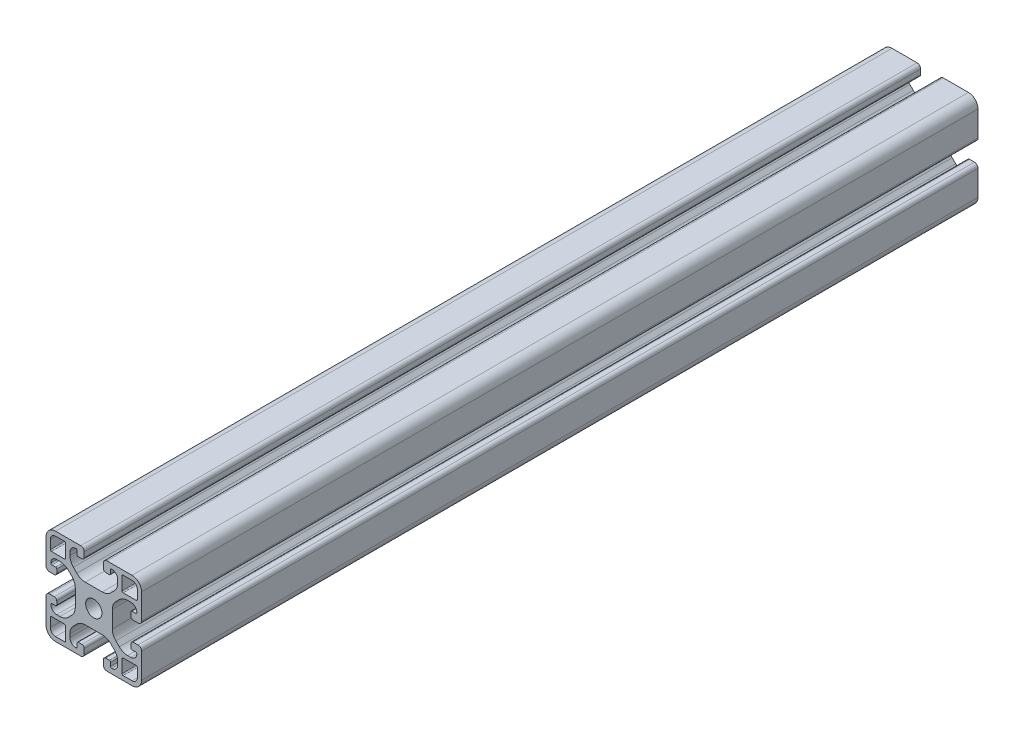
SolidWorks part; units mm, degrees
ref_plane "Plan de face" through (0, 0, 0) normal (0, 0, 1) x (1, 0, 0)
ref_plane "Plan de dessus" through (0, 0, 0) normal (0, 1, 0) x (1, 0, 0)
ref_plane "Plan de droite" through (0, 0, 0) normal (1, 0, 0) x (0, 0, -1)
ref_plane "Plan1" through (0, 0, -30) normal (0, 0, -1) x (-1, 0, 0)
sketch "Esquisse1" plane through (0, 0, -30) normal (0, 0, -1) x (-1, 0, 0)
  line L0 (-4.5, 15) -> (-4.5, 13.5)
  line L1 (-4, 13) -> (-2.5, 13)
  line L2 (-4.5, 10) -> (-5.8076, 10)
  line L3 (-9.3431, 11.4645) -> (-10.7855, 12.9069)
  line L4 (-12.25, 16.4424) -> (-12.25, 23.5576)
  line L5 (-10.7855, 27.0931) -> (-9.3431, 28.5355)
  line L6 (-5.8076, 30) -> (-4.5, 30)
  line L7 (-2.5, 27) -> (-4, 27)
  line L8 (-4.5, 26.5) -> (-4.5, 25)
  line L9 (-3.5, 24) -> (-1.5, 24)
  line L10 (0, 25.5) -> (0, 36)
  line L11 (-4, 40) -> (-14.5, 40)
  line L12 (-16, 38.5) -> (-16, 36.5)
  line L13 (-15, 35.5) -> (-13.5, 35.5)
  line L14 (-13, 36) -> (-13, 37.5)
  line L15 (-10, 35.5) -> (-10, 34.1924)
  line L16 (-11.4645, 30.6569) -> (-12.9069, 29.2145)
  line L17 (-16.4424, 27.75) -> (-23.5576, 27.75)
  line L18 (-27.0931, 29.2145) -> (-28.5355, 30.6569)
  line L19 (-30, 34.1924) -> (-30, 35.5)
  line L20 (-27, 37.5) -> (-27, 36)
  line L21 (-26.5, 35.5) -> (-25, 35.5)
  line L22 (-24, 36.5) -> (-24, 38.5)
  line L23 (-25.5, 40) -> (-36, 40)
  line L24 (-40, 36) -> (-40, 25.5)
  line L25 (-38.5, 24) -> (-36.5, 24)
  line L26 (-35.5, 25) -> (-35.5, 26.5)
  line L27 (-36, 27) -> (-37.5, 27)
  line L28 (-35.5, 30) -> (-34.1924, 30)
  line L29 (-30.6569, 28.5355) -> (-29.2145, 27.0931)
  line L30 (-27.75, 23.5576) -> (-27.75, 16.4424)
  line L31 (-29.2145, 12.9069) -> (-30.6569, 11.4645)
  line L32 (-34.1924, 10) -> (-35.5, 10)
  line L33 (-37.5, 13) -> (-36, 13)
  line L34 (-35.5, 13.5) -> (-35.5, 15)
  line L35 (-36.5, 16) -> (-38.5, 16)
  line L36 (-40, 14.5) -> (-40, 4)
  line L37 (-36, 0) -> (-25.5, 0)
  line L38 (-24, 1.5) -> (-24, 3.5)
  line L39 (-25, 4.5) -> (-26.5, 4.5)
  line L40 (-27, 4) -> (-27, 2.5)
  line L41 (-30, 4.5) -> (-30, 5.8076)
  line L42 (-28.5355, 9.3431) -> (-27.0931, 10.7855)
  line L43 (-23.5576, 12.25) -> (-16.4424, 12.25)
  line L44 (-12.9069, 10.7855) -> (-11.4645, 9.3431)
  line L45 (-10, 5.8076) -> (-10, 4.5)
  line L46 (-13, 2.5) -> (-13, 4)
  line L47 (-13.5, 4.5) -> (-15, 4.5)
  line L48 (-16, 3.5) -> (-16, 1.5)
  line L49 (-14.5, 0) -> (-4, 0)
  line L50 (0, 4) -> (0, 14.5)
  line L51 (-1.5, 16) -> (-3.5, 16)
  line L52 (-4, 1.8) -> (-7.7, 1.8)
  line L53 (-8.2, 2.3) -> (-8.2, 7.7)
  line L54 (-7.7, 8.2) -> (-2.3, 8.2)
  line L55 (-1.8, 7.7) -> (-1.8, 4)
  line L56 (-38.2, 4) -> (-38.2, 7.7)
  line L57 (-37.7, 8.2) -> (-32.3, 8.2)
  line L58 (-31.8, 7.7) -> (-31.8, 2.3)
  line L59 (-32.3, 1.8) -> (-36, 1.8)
  line L60 (-36, 38.2) -> (-32.3, 38.2)
  line L61 (-31.8, 37.7) -> (-31.8, 32.3)
  line L62 (-32.3, 31.8) -> (-37.7, 31.8)
  line L63 (-38.2, 32.3) -> (-38.2, 36)
  line L64 (-1.8, 36) -> (-1.8, 32.3)
  line L65 (-2.3, 31.8) -> (-7.7, 31.8)
  line L66 (-8.2, 32.3) -> (-8.2, 37.7)
  line L67 (-7.7, 38.2) -> (-4, 38.2)
  arc A0 (-4.5, 13.5) -> (-4, 13) centre (-4, 13.5) ccw
  arc A1 (-2.5, 13) -> (-2, 12.5) centre (-2.5, 12.5) cw
  arc A2 (-2, 12.5) -> (-4.5, 10) centre (-4.5, 12.5) cw
  arc A3 (-5.8076, 10) -> (-9.3431, 11.4645) centre (-5.8076, 15) cw
  arc A4 (-10.7855, 12.9069) -> (-12.25, 16.4424) centre (-7.25, 16.4424) cw
  arc A5 (-12.25, 23.5576) -> (-10.7855, 27.0931) centre (-7.25, 23.5576) cw
  arc A6 (-9.3431, 28.5355) -> (-5.8076, 30) centre (-5.8076, 25) cw
  arc A7 (-4.5, 30) -> (-2, 27.5) centre (-4.5, 27.5) cw
  arc A8 (-2, 27.5) -> (-2.5, 27) centre (-2.5, 27.5) cw
  arc A9 (-4, 27) -> (-4.5, 26.5) centre (-4, 26.5) ccw
  arc A10 (-4.5, 25) -> (-3.5, 24) centre (-3.5, 25) ccw
  arc A11 (-1.5, 24) -> (0, 25.5) centre (-1.5, 25.5) ccw
  arc A12 (0, 36) -> (-4, 40) centre (-4, 36) ccw
  arc A13 (-14.5, 40) -> (-16, 38.5) centre (-14.5, 38.5) ccw
  arc A14 (-16, 36.5) -> (-15, 35.5) centre (-15, 36.5) ccw
  arc A15 (-13.5, 35.5) -> (-13, 36) centre (-13.5, 36) ccw
  arc A16 (-13, 37.5) -> (-12.5, 38) centre (-12.5, 37.5) cw
  arc A17 (-12.5, 38) -> (-10, 35.5) centre (-12.5, 35.5) cw
  arc A18 (-10, 34.1924) -> (-11.4645, 30.6569) centre (-15, 34.1924) cw
  arc A19 (-12.9069, 29.2145) -> (-16.4424, 27.75) centre (-16.4424, 32.75) cw
  arc A20 (-23.5576, 27.75) -> (-27.0931, 29.2145) centre (-23.5576, 32.75) cw
  arc A21 (-28.5355, 30.6569) -> (-30, 34.1924) centre (-25, 34.1924) cw
  arc A22 (-30, 35.5) -> (-27.5, 38) centre (-27.5, 35.5) cw
  arc A23 (-27.5, 38) -> (-27, 37.5) centre (-27.5, 37.5) cw
  arc A24 (-27, 36) -> (-26.5, 35.5) centre (-26.5, 36) ccw
  arc A25 (-25, 35.5) -> (-24, 36.5) centre (-25, 36.5) ccw
  arc A26 (-24, 38.5) -> (-25.5, 40) centre (-25.5, 38.5) ccw
  arc A27 (-36, 40) -> (-40, 36) centre (-36, 36) ccw
  arc A28 (-40, 25.5) -> (-38.5, 24) centre (-38.5, 25.5) ccw
  arc A29 (-36.5, 24) -> (-35.5, 25) centre (-36.5, 25) ccw
  arc A30 (-35.5, 26.5) -> (-36, 27) centre (-36, 26.5) ccw
  arc A31 (-37.5, 27) -> (-38, 27.5) centre (-37.5, 27.5) cw
  arc A32 (-38, 27.5) -> (-35.5, 30) centre (-35.5, 27.5) cw
  arc A33 (-34.1924, 30) -> (-30.6569, 28.5355) centre (-34.1924, 25) cw
  arc A34 (-29.2145, 27.0931) -> (-27.75, 23.5576) centre (-32.75, 23.5576) cw
  arc A35 (-27.75, 16.4424) -> (-29.2145, 12.9069) centre (-32.75, 16.4424) cw
  arc A36 (-30.6569, 11.4645) -> (-34.1924, 10) centre (-34.1924, 15) cw
  arc A37 (-35.5, 10) -> (-38, 12.5) centre (-35.5, 12.5) cw
  arc A38 (-38, 12.5) -> (-37.5, 13) centre (-37.5, 12.5) cw
  arc A39 (-36, 13) -> (-35.5, 13.5) centre (-36, 13.5) ccw
  arc A40 (-35.5, 15) -> (-36.5, 16) centre (-36.5, 15) ccw
  arc A41 (-38.5, 16) -> (-40, 14.5) centre (-38.5, 14.5) ccw
  arc A42 (-40, 4) -> (-36, 0) centre (-36, 4) ccw
  arc A43 (-25.5, 0) -> (-24, 1.5) centre (-25.5, 1.5) ccw
  arc A44 (-24, 3.5) -> (-25, 4.5) centre (-25, 3.5) ccw
  arc A45 (-26.5, 4.5) -> (-27, 4) centre (-26.5, 4) ccw
  arc A46 (-27, 2.5) -> (-27.5, 2) centre (-27.5, 2.5) cw
  arc A47 (-27.5, 2) -> (-30, 4.5) centre (-27.5, 4.5) cw
  arc A48 (-30, 5.8076) -> (-28.5355, 9.3431) centre (-25, 5.8076) cw
  arc A49 (-27.0931, 10.7855) -> (-23.5576, 12.25) centre (-23.5576, 7.25) cw
  arc A50 (-16.4424, 12.25) -> (-12.9069, 10.7855) centre (-16.4424, 7.25) cw
  arc A51 (-11.4645, 9.3431) -> (-10, 5.8076) centre (-15, 5.8076) cw
  arc A52 (-10, 4.5) -> (-12.5, 2) centre (-12.5, 4.5) cw
  arc A53 (-12.5, 2) -> (-13, 2.5) centre (-12.5, 2.5) cw
  arc A54 (-13, 4) -> (-13.5, 4.5) centre (-13.5, 4) ccw
  arc A55 (-15, 4.5) -> (-16, 3.5) centre (-15, 3.5) ccw
  arc A56 (-16, 1.5) -> (-14.5, 0) centre (-14.5, 1.5) ccw
  arc A57 (-4, 0) -> (0, 4) centre (-4, 4) ccw
  arc A58 (0, 14.5) -> (-1.5, 16) centre (-1.5, 14.5) ccw
  arc A59 (-3.5, 16) -> (-4.5, 15) centre (-3.5, 15) ccw
  circle A60 centre (-20, 20) radius 3.4
  arc A61 (-1.8, 4) -> (-4, 1.8) centre (-4, 4) cw
  arc A62 (-7.7, 1.8) -> (-8.2, 2.3) centre (-7.7, 2.3) cw
  arc A63 (-8.2, 7.7) -> (-7.7, 8.2) centre (-7.7, 7.7) cw
  arc A64 (-2.3, 8.2) -> (-1.8, 7.7) centre (-2.3, 7.7) cw
  arc A65 (-36, 1.8) -> (-38.2, 4) centre (-36, 4) cw
  arc A66 (-38.2, 7.7) -> (-37.7, 8.2) centre (-37.7, 7.7) cw
  arc A67 (-32.3, 8.2) -> (-31.8, 7.7) centre (-32.3, 7.7) cw
  arc A68 (-31.8, 2.3) -> (-32.3, 1.8) centre (-32.3, 2.3) cw
  arc A69 (-38.2, 36) -> (-36, 38.2) centre (-36, 36) cw
  arc A70 (-32.3, 38.2) -> (-31.8, 37.7) centre (-32.3, 37.7) cw
  arc A71 (-31.8, 32.3) -> (-32.3, 31.8) centre (-32.3, 32.3) cw
  arc A72 (-37.7, 31.8) -> (-38.2, 32.3) centre (-37.7, 32.3) cw
  arc A73 (-4, 38.2) -> (-1.8, 36) centre (-4, 36) cw
  arc A74 (-1.8, 32.3) -> (-2.3, 31.8) centre (-2.3, 32.3) cw
  arc A75 (-7.7, 31.8) -> (-8.2, 32.3) centre (-7.7, 32.3) cw
  arc A76 (-8.2, 37.7) -> (-7.7, 38.2) centre (-7.7, 37.7) cw
extrude "Boss.-Extru.1" add sketch "Esquisse1" against normal blind 350
